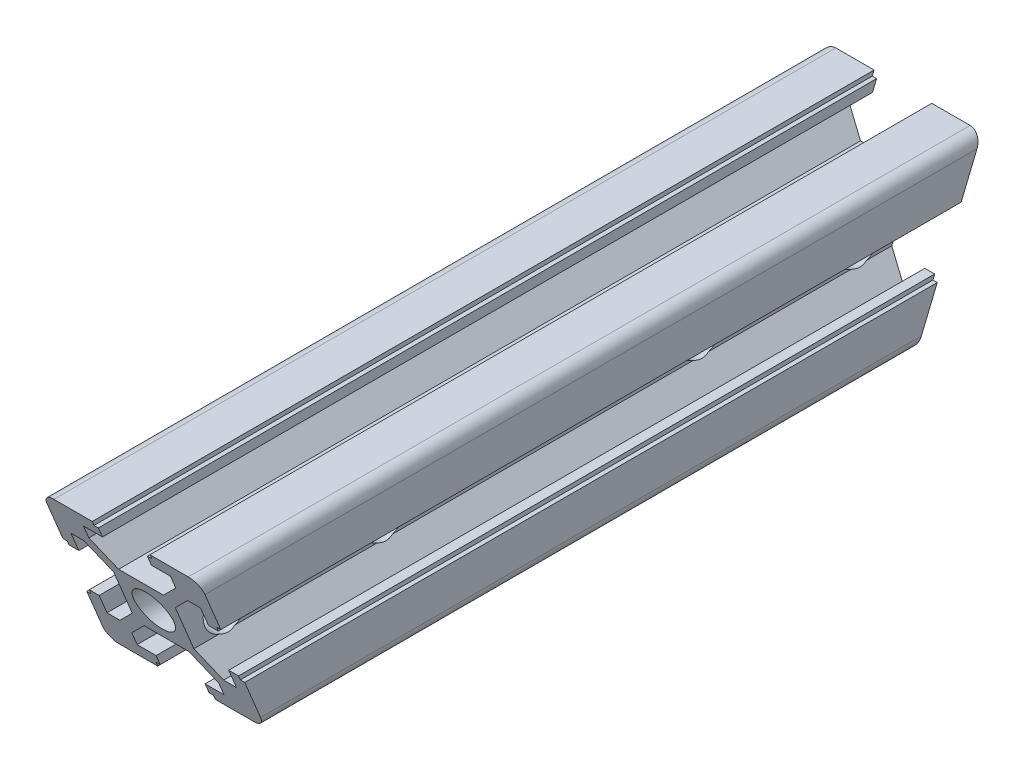
SolidWorks part; units mm, degrees
material "6063-T5"
ref_plane "前视基准面" through (0, 0, 0) normal (0, 0, 1) x (1, 0, 0)
ref_plane "上视基准面" through (0, 0, 0) normal (0, 1, 0) x (1, 0, 0)
ref_plane "右视基准面" through (0, 0, 0) normal (1, 0, 0) x (0, 0, -1)
sketch "草图2" plane through (0, 0, 0) normal (0, 0, 1) x (1, 0, 0)
  line L0 (-3.9, 2.8393) -> (-6.5607, 5.5)
  line L1 (-2.8393, 3.9) -> (2.8393, 3.9)
  line L2 (-3.9, 2.8393) -> (-3.9, -2.8393)
  line L3 (-2.8393, -3.9) -> (2.8393, -3.9)
  line L4 (3.9, 2.8393) -> (3.9, -2.8393)
  line L5 (-3.9, 3.9) -> (3.9, -3.9) construction
  line L6 (-3.9, -3.9) -> (3.9, 3.9) construction
  line L7 (-2.8393, 3.9) -> (-5.5, 6.5607)
  line L8 (-5.5, 6.5607) -> (-5.5, 8.2)
  line L9 (-5.5, 8.2) -> (-3.1, 8.2)
  line L10 (-3.1, 8.2) -> (-3.1, 9.45)
  line L11 (-3.1, 9.45) -> (-3.65, 9.45)
  line L12 (-3.65, 9.45) -> (-3.65, 10)
  line L13 (-3.65, 10) -> (-8.5, 10)
  line L14 (-6.5607, 5.5) -> (-8.2, 5.5)
  line L15 (-10, 3.65) -> (-10, 8.5)
  line L16 (-9.45, 3.65) -> (-10, 3.65)
  line L17 (-9.45, 3.1) -> (-9.45, 3.65)
  line L18 (-8.2, 3.1) -> (-9.45, 3.1)
  line L19 (-8.2, 5.5) -> (-8.2, 3.1)
  line L20 (2.8393, 3.9) -> (5.5, 6.5607)
  line L21 (3.9, 2.8393) -> (6.5607, 5.5)
  line L22 (6.5607, 5.5) -> (8.2, 5.5)
  line L23 (8.2, 5.5) -> (8.2, 3.1)
  line L24 (8.2, 3.1) -> (9.45, 3.1)
  line L25 (9.45, 3.1) -> (9.45, 3.65)
  line L26 (9.45, 3.65) -> (10, 3.65)
  line L27 (10, 3.65) -> (10, 8.5)
  line L28 (5.5, 6.5607) -> (5.5, 8.2)
  line L29 (3.65, 10) -> (8.5, 10)
  line L30 (3.65, 9.45) -> (3.65, 10)
  line L31 (3.1, 9.45) -> (3.65, 9.45)
  line L32 (3.1, 8.2) -> (3.1, 9.45)
  line L33 (5.5, 8.2) -> (3.1, 8.2)
  line L34 (3.9, -2.8393) -> (6.5607, -5.5)
  line L35 (2.8393, -3.9) -> (5.5, -6.5607)
  line L36 (5.5, -6.5607) -> (5.5, -8.2)
  line L37 (5.5, -8.2) -> (3.1, -8.2)
  line L38 (3.1, -8.2) -> (3.1, -9.45)
  line L39 (3.1, -9.45) -> (3.65, -9.45)
  line L40 (3.65, -9.45) -> (3.65, -10)
  line L41 (3.65, -10) -> (8.5, -10)
  line L42 (6.5607, -5.5) -> (8.2, -5.5)
  line L43 (10, -3.65) -> (10, -8.5)
  line L44 (9.45, -3.65) -> (10, -3.65)
  line L45 (9.45, -3.1) -> (9.45, -3.65)
  line L46 (8.2, -3.1) -> (9.45, -3.1)
  line L47 (8.2, -5.5) -> (8.2, -3.1)
  line L48 (-2.8393, -3.9) -> (-5.5, -6.5607)
  line L49 (-3.9, -2.8393) -> (-6.5607, -5.5)
  line L50 (-6.5607, -5.5) -> (-8.2, -5.5)
  line L51 (-8.2, -5.5) -> (-8.2, -3.1)
  line L52 (-8.2, -3.1) -> (-9.45, -3.1)
  line L53 (-9.45, -3.1) -> (-9.45, -3.65)
  line L54 (-9.45, -3.65) -> (-10, -3.65)
  line L55 (-10, -3.65) -> (-10, -8.5)
  line L56 (-5.5, -6.5607) -> (-5.5, -8.2)
  line L57 (-3.65, -10) -> (-8.5, -10)
  line L58 (-3.65, -9.45) -> (-3.65, -10)
  line L59 (-3.1, -9.45) -> (-3.65, -9.45)
  line L60 (-3.1, -8.2) -> (-3.1, -9.45)
  line L61 (-5.5, -8.2) -> (-3.1, -8.2)
  circle A0 centre (0, 0) radius 2.55
  arc A1 (-8.5, 10) -> (-10, 8.5) centre (-8.5, 8.5) ccw
  arc A2 (10, 8.5) -> (8.5, 10) centre (8.5, 8.5) ccw
  arc A3 (8.5, -10) -> (10, -8.5) centre (8.5, -8.5) ccw
  arc A4 (-10, -8.5) -> (-8.5, -10) centre (-8.5, -8.5) ccw
  point P25 (-10, 10)
  point P79 (0, 0)
  dimension "D1" = 5.1
  dimension "D9" = 1.5
  dimension "D2" = 7.8
  dimension "D3" = 1.5
  dimension "D4" = 10
  dimension "D5" = 3.1
  dimension "D6" = 0.55
  dimension "D7" = 1.8
  dimension "D8" = 5.5
  dimension "D11" = 3.9
  dimension "D10" = 4
extrude "凸台-拉伸1" add sketch "草图2" along normal blind 98.99
sketch "草图3" plane through (10, 0, 0) normal (1, 0, 0) x (0, 0, -1)
  line L0 (0, 0) -> (-98.99, 0) construction
  line L1 (-98.99, -2.8393) -> (-98.99, 2.8393) construction
  line L2 (-49.495, 8.5) -> (-49.495, -8.5) construction
  line L3 (-98.99, 8.5) -> (0, 8.5) construction
  line L4 (-98.99, -8.5) -> (0, -8.5) construction
  circle A2 centre (-29.495, 0) radius 3
  circle A3 centre (-69.495, 0) radius 3
  point P17 (-49.495, 0)
  dimension "D1" = 6
  dimension "D2" = 6
  dimension "D3" = 20
  dimension "D4" = 20
extrude "切除-拉伸1" cut sketch "草图3" against normal through all
ref_plane "基准面1" through (8.5, -10, 98.99) normal (0, 0, -1) x (-1, 0, 0)
sketch "草图5" plane through (10, 0, 0) normal (1, 0, 0) x (0, 0, -1)
  line L0 (-98.99, 10) -> (-90.7057, -10)
  line L1 (-98.99, -10) -> (0, -10) construction
  line L2 (0, 10) -> (-8.2843, -10)
  line L5 (-98.99, 10) -> (-98.99, -10)
  line L6 (-98.99, -10) -> (-90.7057, -10)
  line L7 (0, 10) -> (0, -10)
  line L8 (0, -10) -> (-8.2843, -10)
  dimension "D1" = 112.5
  dimension "D2" = 112.5
extrude "切除-拉伸2" cut sketch "草图5" against normal blind 20
sketch "草图6" plane through (10, 0, 0) normal (1, 0, 0) x (0, 0, -1)
  line L0 (-4.1421, 0) -> (-94.8479, 0) construction
  line L1 (-2.966, 2.8393) -> (-5.3182, -2.8393) construction
  line L2 (-93.6718, -2.8393) -> (-96.024, 2.8393) construction
  circle A0 centre (-9.495, 0) radius 3
  circle A1 centre (-89.495, 0) radius 3
  point P10 (-49.495, 0)
  dimension "D1" = 6
  dimension "D2" = 6
  dimension "D3" = 40
  dimension "D4" = 40
extrude "切除-拉伸3" cut sketch "草图6" against normal blind 20
